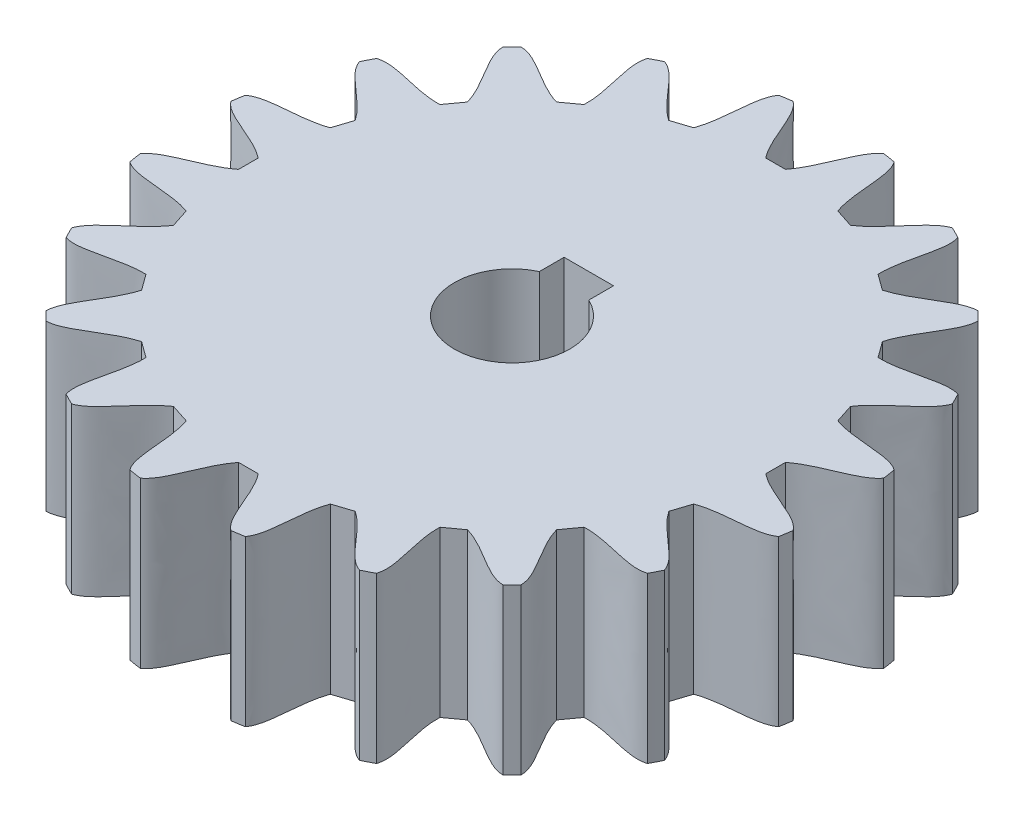
SolidWorks part; units mm, degrees
ref_plane "Plan de face" through (0, 0, 0) normal (0, 0, 1) x (1, 0, 0)
ref_plane "Plan de dessus" through (0, 0, 0) normal (0, 1, 0) x (1, 0, 0)
ref_plane "Plan de droite" through (0, 0, 0) normal (1, 0, 0) x (0, 0, -1)
sketch "Esquisse1" plane through (0, 0, 0) normal (0, 1, 0) x (1, 0, 0)
  line L1 (-1.5, 3.1623) -> (1.5, 3.1623) construction
  line L2 (-1.5, 3.1623) -> (-1.5, 4.6623)
  line L3 (-1.5, 4.6623) -> (1.5, 4.6623)
  line L4 (1.5, 4.6623) -> (1.5, 3.1623)
  circle A0 centre (0, 0) radius 20
  arc A1 (-1.5, 3.1623) -> (1.5, 3.1623) centre (0, 0) ccw
  circle A2 centre (0, 0) radius 18 construction
  dimension "D1" = 40
  dimension "D2" = 3
  dimension "D4" = 1.5
  dimension "D5" = 3.5
  dimension "D3" = 36
extrude "Boss.-Extru.2" add sketch "Esquisse1" along normal blind 10
sketch "Esquisse3" plane through (0, 10, 0) normal (0, 1, 0) x (1, 0, 0)
  line L0 (0, -13.5087) -> (0, 78.1714) construction
  line L1 (-0.6, 16) -> (0.6, 16)
  line L2 (-0.6, 16) -> (-1.6252, 17.3178) construction
  line L3 (-1.6252, 17.3178) -> (-1.9326, 19.4782) construction
  line L4 (-1.9326, 19.4782) -> (-2.9487, 19.9215) construction
  line L5 (0.6, 16) -> (1.6252, 17.3178) construction
  line L6 (1.6252, 17.3178) -> (1.9326, 19.4782) construction
  line L7 (1.9326, 19.4782) -> (2.9487, 19.9215) construction
  line L8 (0, 0) -> (0, 104.466) construction
  arc A0 (-2.9487, 19.9215) -> (2.9487, 19.9215) centre (0, 20) cw
  circle A1 centre (0, 0) radius 20 construction
  spline S0 degree 3 poles (-0.6, 16) (-1.6252, 17.3178) (-1.9326, 19.4782) (-2.9487, 19.9215) knots 0 0 0 0 1 1 1 1
  spline S1 degree 3 poles (0.6, 16) (1.6252, 17.3178) (1.9326, 19.4782) (2.9487, 19.9215) knots 0 0 0 0 1 1 1 1
  point P4 (0, 16)
  point P19 (0, 20)
  dimension "D2" = 1.2
  dimension "D4" = 3.9215
  dimension "D7" = 4
extrude "Enlèv. mat.-Extru.2" cut sketch "Esquisse3" against normal blind 100
pattern_circular "Répétition circulaire3" count 20 every 18 about axis through (0, 10, 0) along (0, 1, 0) of "Enlèv. mat.-Extru.2"
